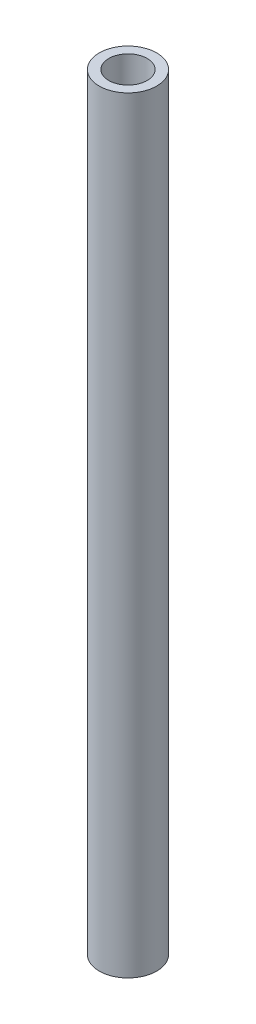
SolidWorks part; units mm, degrees
ref_plane "前视基准面" through (0, 0, 0) normal (0, 0, 1) x (1, 0, 0)
ref_plane "上视基准面" through (0, 0, 0) normal (0, 1, 0) x (1, 0, 0)
ref_plane "右视基准面" through (0, 0, 0) normal (1, 0, 0) x (0, 0, -1)
sketch "草图1" plane through (0, 0, 0) normal (0, 1, 0) x (1, 0, 0)
  circle A0 centre (0, 0) radius 2
  circle A1 centre (0, 0) radius 3
extrude "凸台-拉伸1" add sketch "草图1" along normal blind 80
